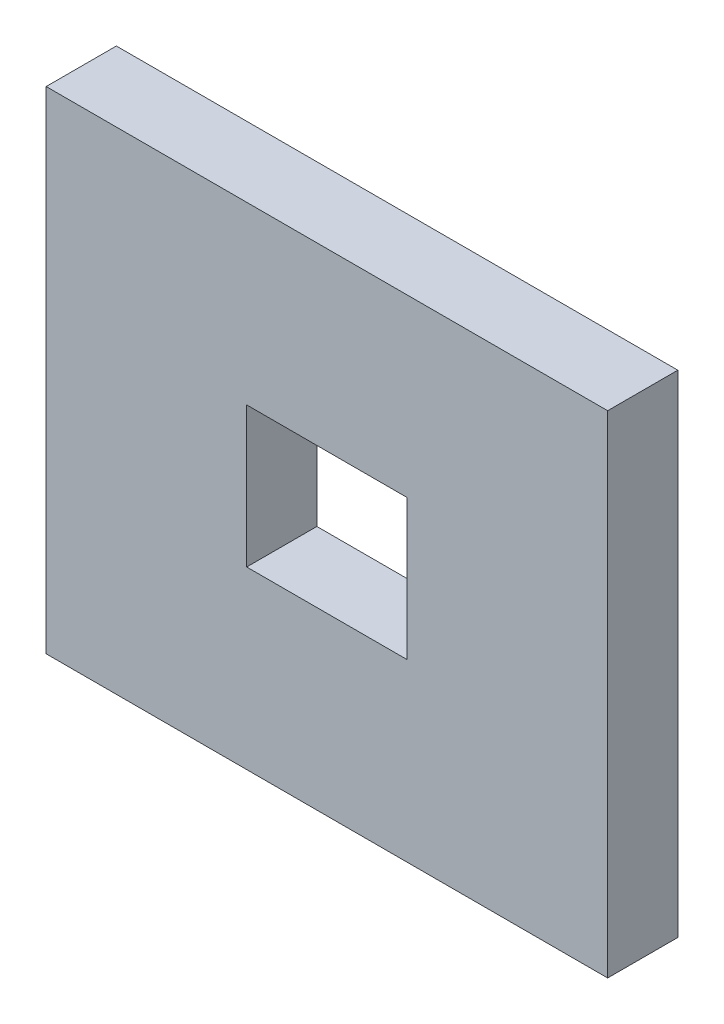
SolidWorks part; units mm, degrees
material "Maple"
ref_plane "Front Plane" through (0, 0, 0) normal (0, 0, 1) x (1, 0, 0)
ref_plane "Top Plane" through (0, 0, 0) normal (0, 1, 0) x (1, 0, 0)
ref_plane "Right Plane" through (0, 0, 0) normal (1, 0, 0) x (0, 0, -1)
sketch "Sketch1" plane through (0, 0, 0) normal (0, 0, 1) x (1, 0, 0)
  line L1 (40, 35) -> (-40, 35)
  line L2 (40, 35) -> (40, -35)
  line L3 (40, -35) -> (-40, -35)
  line L4 (-40, 35) -> (-40, -35)
  line L5 (40, 35) -> (-40, -35) construction
  line L6 (40, -35) -> (-40, 35) construction
  line L7 (11.4286, 10) -> (-11.4286, 10)
  line L8 (11.4286, 10) -> (11.4286, -10)
  line L9 (11.4286, -10) -> (-11.4286, -10)
  line L10 (-11.4286, 10) -> (-11.4286, -10)
  line L11 (11.4286, 10) -> (-11.4286, -10) construction
  line L12 (11.4286, -10) -> (-11.4286, 10) construction
  point P0 (0, 0)
  point P6 (0, 0)
  dimension "D1" = 80
  dimension "D2" = 70
  dimension "D3" = 20
extrude "Boss-Extrude1" add sketch "Sketch1" along normal blind 10
